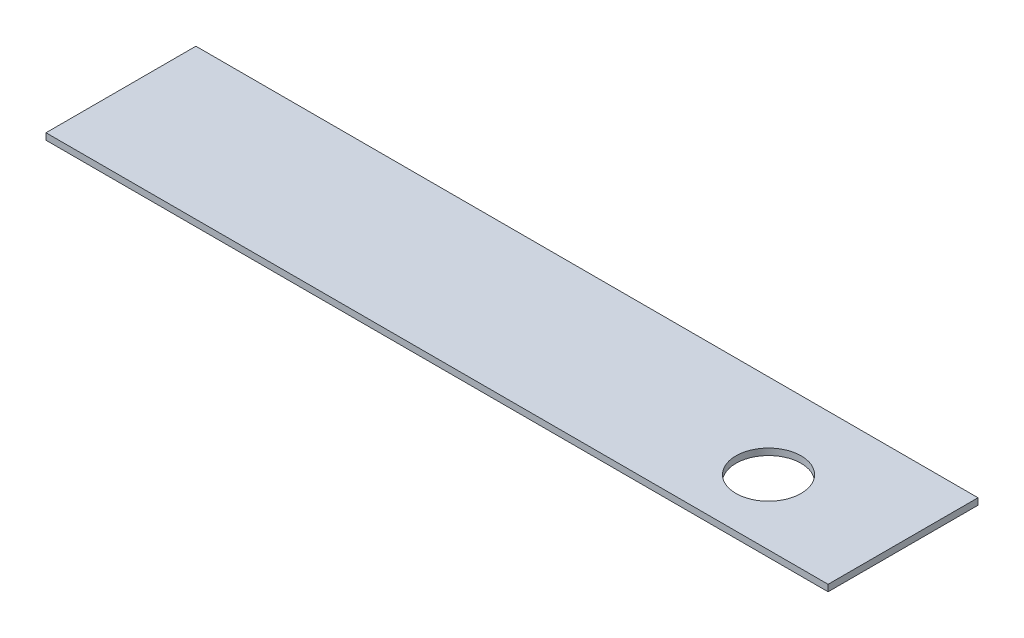
SolidWorks part; units mm, degrees
ref_plane "Front Plane" through (0, 0, 0) normal (0, 0, 1) x (1, 0, 0)
ref_plane "Top Plane" through (0, 0, 0) normal (0, 1, 0) x (1, 0, 0)
ref_plane "Right Plane" through (0, 0, 0) normal (1, 0, 0) x (0, 0, -1)
sketch "Sketch1" plane through (0, 0, 0) normal (0, 0, 1) x (1, 0, 0)
  line L0 (299.49, -216.4294) -> (59.49, -216.4294) construction
  line L2 (299.49, -216.4294) -> (59.49, -216.4294)
  line L3 (299.49, -218.4294) -> (59.49, -218.4294)
  line L4 (299.49, -216.4294) -> (299.49, -218.4294)
  line L5 (59.49, -216.4294) -> (59.49, -218.4294)
  dimension "D1" = 2
extrude "Boss-Extrude1" add sketch "Sketch1" along normal up to surface (46 mm away)
sketch "Sketch2" plane through (0, -216.4294, 0) normal (0, 1, 0) x (1, 0, 0)
  line L0 (299.49, -46) -> (59.49, -46) construction
  circle A0 centre (261.2074, -26) radius 10
  dimension "D2" = 20
  dimension "D1" = 20
extrude "Cut-Extrude1" cut sketch "Sketch2" against normal up to surface (2 mm away) up to face at (179.49, -218.4294, 23)
